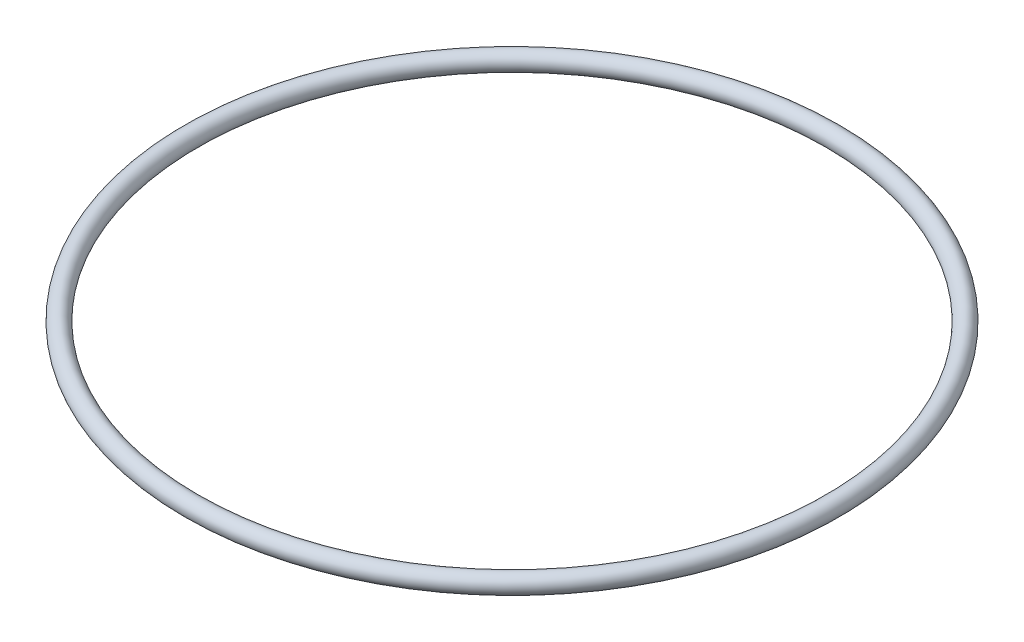
SolidWorks part; units mm, degrees
ref_plane "Front Plane" through (0, 0, 0) normal (0, 0, 1) x (1, 0, 0)
ref_plane "Top Plane" through (0, 0, 0) normal (0, 1, 0) x (1, 0, 0)
ref_plane "Right Plane" through (0, 0, 0) normal (1, 0, 0) x (0, 0, -1)
sketch "Sketch1" plane through (0, 0, 0) normal (0, 0, 1) x (1, 0, 0)
  line L0 (0, 0) -> (0, 23.2778) construction
  circle A0 centre (35, 0) radius 1
  dimension "D1" = 2
  dimension "D2" = 35
revolve "Revolve1" add sketch "Sketch1" angle 360 about L0
